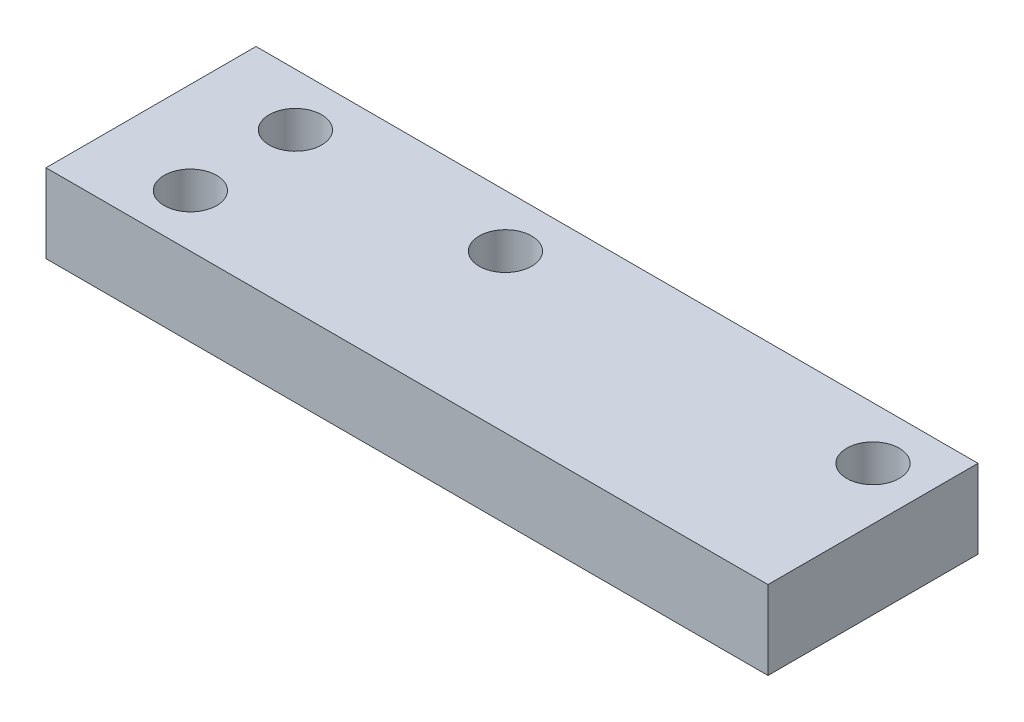
SolidWorks part; units mm, degrees
material "Stainless Steel (ferritic)"
ref_plane "Front Plane" through (0, 0, 0) normal (0, 0, 1) x (1, 0, 0)
ref_plane "Top Plane" through (0, 0, 0) normal (0, 1, 0) x (1, 0, 0)
ref_plane "Right Plane" through (0, 0, 0) normal (1, 0, 0) x (0, 0, -1)
sketch "Sketch2" plane through (0, 0, 0) normal (0, 1, 0) x (1, 0, 0)
  line L0 (51, 0) -> (51, -16) construction
  line L1 (0, 0) -> (55, 0)
  line L2 (0, 0) -> (0, -16)
  line L3 (0, -16) -> (55, -16)
  line L4 (55, 0) -> (55, -16)
  line L5 (23, 0) -> (23, -16) construction
  line L6 (23, -4) -> (51, -4) construction
  line L7 (51, -4) -> (55, -4) construction
  line L8 (23, -4) -> (19, -4) construction
  line L9 (19, 0) -> (19, -16) construction
  line L10 (7, 0) -> (7, -4) construction
  line L11 (0, -4) -> (7, -4) construction
  line L12 (7, -4) -> (19, -4) construction
  line L13 (7, -4) -> (7, -12) construction
  line L14 (7, -12) -> (7, -16) construction
  circle A0 centre (23, -4) radius 2
  circle A1 centre (51, -4) radius 2
  circle A2 centre (7, -4) radius 2
  circle A3 centre (7, -12) radius 2
  dimension "D5" = 4
  dimension "D6" = 4
  dimension "D8" = 4
  dimension "D9" = 4
  dimension "D1" = 55
  dimension "D2" = 16
  dimension "D3" = 36
  dimension "D4" = 28
  dimension "D7" = 4
  dimension "D10" = 12
  dimension "D11" = 8
extrude "Boss-Extrude1" add sketch "Sketch2" along normal blind 6
